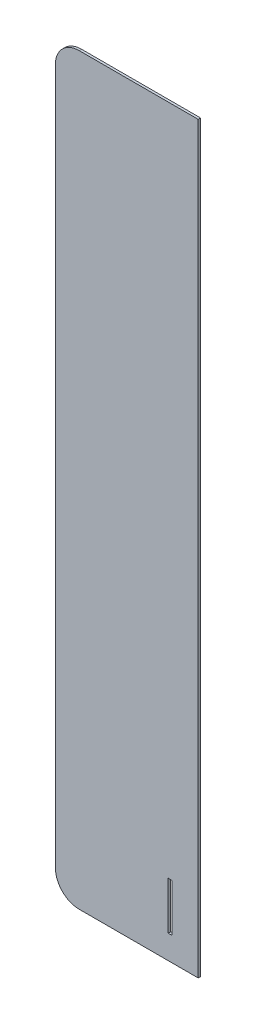
SolidWorks part; units mm, degrees
material "Резина"
ref_plane "Спереди" through (0, 0, 0) normal (0, 0, 1) x (1, 0, 0)
ref_plane "Сверху" through (0, 0, 0) normal (0, 1, 0) x (1, 0, 0)
ref_plane "Справа" through (0, 0, 0) normal (1, 0, 0) x (0, 0, -1)
other "Configuration Table"
sketch "Эскиз1" plane through (0, 0, 0) normal (0, 0, 1) x (1, 0, 0)
  line L1 (-150, -781) -> (150, -781)
  line L2 (-150, -781) -> (-150, 781)
  line L3 (-150, 781) -> (150, 781)
  line L4 (150, -781) -> (150, 781)
  line L5 (0, 781) -> (0, -781) construction
  line L6 (-150, 0) -> (150, 0) construction
  point P0 (0, 0)
  dimension "D1" = 300
  dimension "D2" = 1562
extrude "Бобышка-Вытянуть1" add sketch "Эскиз1" along normal blind 5
fillet "Скругление1" radius 50 2 edges at (-150, -781, 2.5) (-150, 781, 2.5)
sketch "Эскиз2" plane through (0, 0, 5) normal (0, 0, 1) x (1, 0, 0)
  line L1 (87, -631) -> (95, -631)
  line L2 (87, -631) -> (87, -731)
  line L3 (87, -731) -> (95, -731)
  line L4 (95, -631) -> (95, -731)
  line L5 (-100, -781) -> (150, -781) construction
  line L6 (150, -781) -> (150, 781) construction
  dimension "D1" = 50
  dimension "D2" = 55
  dimension "D3" = 8
  dimension "100" = 100
extrude "Вырез-Вытянуть1" cut sketch "Эскиз2" against normal through all both and the other way through all
